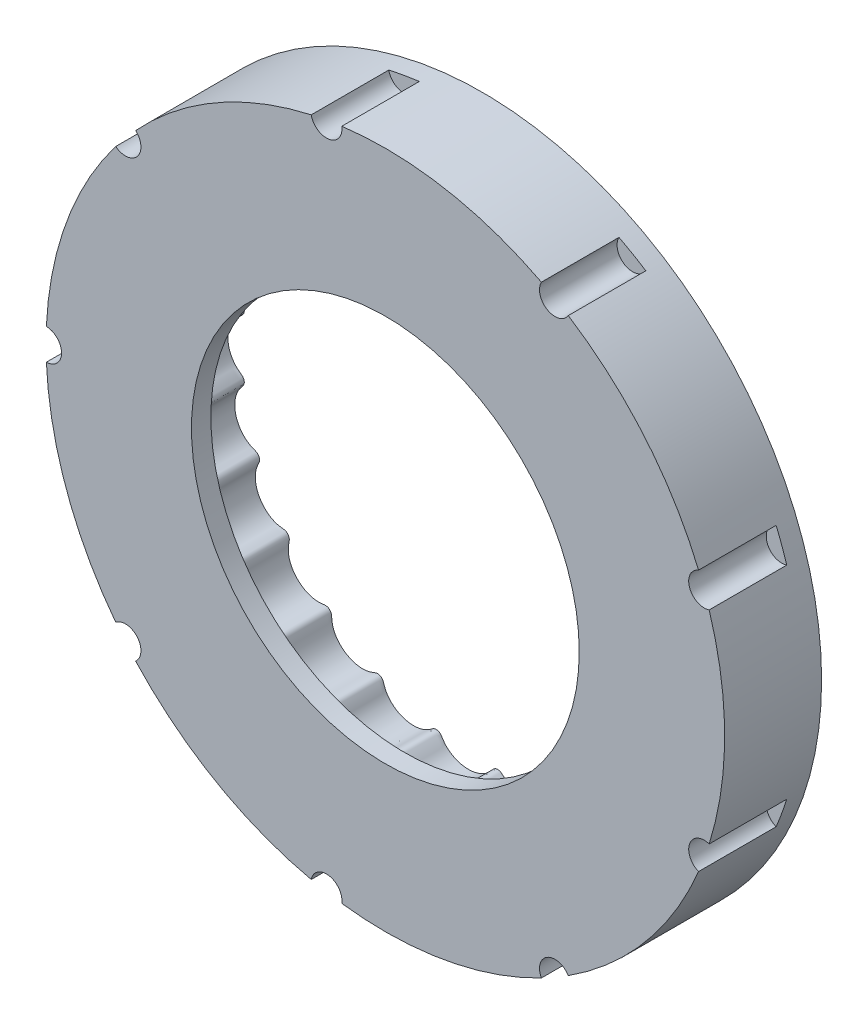
SolidWorks part; units mm, degrees
ref_plane "Plan de face" through (0, 0, 0) normal (0, 0, 1) x (1, 0, 0)
ref_plane "Plan de dessus" through (0, 0, 0) normal (0, 1, 0) x (1, 0, 0)
ref_plane "Plan de droite" through (0, 0, 0) normal (1, 0, 0) x (0, 0, -1)
sketch "Esquisse1" plane through (0, 0, 0) normal (0, 0, 1) x (1, 0, 0)
  line L0 (-1000, 0) -> (49000, 0) construction
  circle A1 centre (0, 0) radius 35
  spline S0 degree 4 poles (24.1426, 6.7991) (24.1177, 6.7609) (24.0692, 6.6836) (24.0004, 6.5645) (23.9483, 6.387) (23.9505, 6.1855) (24.0272, 5.9803) (24.1778, 5.8151) (24.3705, 5.7045) (24.5983, 5.5844) (24.8479, 5.4264) (25.1139, 5.2067) (25.3819, 4.9129) (25.6102, 4.583) (25.7961, 4.2235) (25.9371, 3.8403) (26.0305, 3.4429) (26.0756, 3.0373) (26.0716, 2.6291) (26.0179, 2.2244) (25.9151, 1.834) (25.7643, 1.4641) (25.5917, 1.1641) (25.4167, 0.9296) (25.2526, 0.7496) (25.1124, 0.6144) (24.9828, 0.4987) (24.8797, 0.3844) (24.8179, 0.2829) (24.7848, 0.2051) (24.7673, 0.1461) (24.7588, 0.1043) (24.7529, 0.0597) (24.7496, 0.0145) (24.7496, -0.0147) (24.7529, -0.06) (24.7589, -0.1048) (24.7675, -0.1468) (24.7852, -0.2061) (24.8185, -0.2842) (24.8808, -0.3859) (24.9847, -0.5005) (25.1148, -0.6166) (25.2554, -0.7525) (25.4198, -0.9333) (25.595, -1.1691) (25.7689, -1.4729) (25.9207, -1.8497) (26.0235, -2.2499) (26.0747, -2.6669) (26.0733, -3.0863) (26.0204, -3.5015) (25.917, -3.9063) (25.7644, -4.2943) (25.5662, -4.6548) (25.3259, -4.9815) (25.0816, -5.2331) (24.8519, -5.4186) (24.6671, -5.5402) (24.5395, -5.6139) (24.4102, -5.6846) (24.274, -5.758) (24.12, -5.8678) (23.9899, -6.0503) (23.9364, -6.2751) (23.9692, -6.4958) (24.0654, -6.6843) (24.1784, -6.8519) (24.2801, -7.019) (24.3936, -7.2353) (24.5034, -7.5077) (24.5951, -7.8454) (24.647, -8.2482) (24.6457, -8.6612) (24.576, -9.1855) (24.4176, -9.6961) (24.1747, -10.1766) (23.852, -10.6101) (23.5588, -10.9098) (23.241, -11.1578) (22.9466, -11.3291) (22.6921, -11.4408) (22.4727, -11.5135) (22.2939, -11.5615) (22.1013, -11.606) (21.9021, -11.6816) (21.7285, -11.8281) (21.6209, -12.0388) (21.6016, -12.2637) (21.6505, -12.4693) (21.7183, -12.6598) (21.7746, -12.8471) (21.8297, -13.085) (21.8672, -13.3762) (21.8707, -13.726) (21.8195, -14.1287) (21.7142, -14.528) (21.5148, -15.0178) (21.2331, -15.4721) (20.8771, -15.876) (20.4557, -16.2144) (20.0964, -16.4307) (19.7262, -16.5906) (19.3981, -16.6821) (19.1236, -16.7259) (18.8929, -16.7409) (18.7078, -16.7424) (18.5101, -16.7378) (18.2984, -16.7644) (18.0955, -16.8669) (17.9421, -17.0472) (17.8714, -17.2614) (17.8702, -17.4725) (17.8883, -17.6738) (17.8957, -17.8692) (17.8889, -18.1133) (17.8517, -18.4044) (17.7668, -18.7438) (17.6158, -19.1205) (17.4134, -19.4803) (17.1623, -19.8168) (16.8685, -20.1221) (16.5358, -20.3908) (16.1684, -20.6173) (15.771, -20.7957) (15.3688, -20.9145) (14.9702, -20.976) (14.6296, -20.9817) (14.3529, -20.9549) (14.1259, -20.9112) (13.9464, -20.866) (13.7558, -20.8128) (13.5435, -20.7889) (13.3222, -20.8417) (13.1314, -20.9817) (13.013, -21.1736) (12.9618, -21.3782) (12.9291, -21.5776) (12.887, -21.7685) (12.8188, -22.0029) (12.7093, -22.2752) (12.5416, -22.5821) (12.3006, -22.9086) (12.0142, -23.2057) (11.6866, -23.4682) (11.3255, -23.6897) (10.9359, -23.8661) (10.5233, -23.9928) (10.0937, -24.0655) (9.6744, -24.0792) (9.2731, -24.0382) (8.942, -23.9578) (8.6811, -23.862) (8.4724, -23.7624) (8.31, -23.6735) (8.1383, -23.575) (7.9372, -23.5018) (7.7049, -23.5021) (7.4781, -23.6007) (7.3169, -23.7729) (7.2208, -23.9706) (7.1156, -24.2034) (6.9743, -24.4604) (6.773, -24.7375) (6.4979, -25.0224) (6.1834, -25.2709) (5.8357, -25.4797) (5.4603, -25.6452) (5.0615, -25.7656) (4.6447, -25.8371) (4.2157, -25.8559) (3.7816, -25.8181) (3.3723, -25.7258) (2.9942, -25.5849) (2.6941, -25.4236) (2.4656, -25.2649) (2.2891, -25.1158) (2.1537, -24.9891) (2.0123, -24.8511) (1.8324, -24.7331) (1.553, -24.6659) (1.2621, -24.7546) (1.0754, -24.9576) (0.8891, -25.1941) (0.6967, -25.4018) (0.4476, -25.6153) (0.1257, -25.8218) (-0.2246, -25.9871) (-0.599, -26.1091) (-0.9909, -26.1853) (-1.3919, -26.2146) (-1.7962, -26.1958) (-2.1981, -26.1285) (-2.5915, -26.0119) (-2.9628, -25.849) (-3.3062, -25.6424) (-3.6154, -25.3948) (-3.8503, -25.1456) (-4.0231, -24.9087) (-4.157, -24.6911) (-4.2763, -24.5066) (-4.4563, -24.3545) (-4.6931, -24.2829) (-4.9238, -24.3097) (-5.115, -24.4061) (-5.2732, -24.5252) (-5.423, -24.6339) (-5.6174, -24.7592) (-5.864, -24.8876) (-6.1822, -25.0094) (-6.5751, -25.1011) (-6.9928, -25.1407) (-7.4281, -25.1231) (-7.8512, -25.0501) (-8.2556, -24.9263) (-8.636, -24.7563) (-8.9874, -24.5444) (-9.3058, -24.2932) (-9.5861, -24.0067) (-9.8229, -23.6892) (-9.9872, -23.3887) (-10.0948, -23.1158) (-10.1696, -22.8715) (-10.2411, -22.6635) (-10.3812, -22.4737) (-10.595, -22.3493) (-10.8256, -22.322) (-11.0338, -22.3709) (-11.2164, -22.4474) (-11.3887, -22.5149) (-11.6084, -22.5872) (-11.8793, -22.649) (-12.2179, -22.6866) (-12.6212, -22.6763) (-13.0353, -22.6095) (-13.4521, -22.4829) (-13.8453, -22.3049) (-14.2094, -22.0805) (-14.5395, -21.815) (-14.8313, -21.5131) (-15.0777, -21.1819) (-15.2753, -20.8275) (-15.4026, -20.5017) (-15.4765, -20.2177) (-15.5143, -19.9765) (-15.5318, -19.7817) (-15.5392, -19.5798) (-15.5656, -19.3704) (-15.6608, -19.166) (-15.8341, -19.0047) (-16.0476, -18.9266) (-16.2611, -18.9252) (-16.4568, -18.9543) (-16.6405, -18.9763) (-16.8713, -18.9908) (-17.1491, -18.9822) (-17.4862, -18.9332) (-17.8737, -18.8216) (-18.2576, -18.6527) (-18.6291, -18.4253) (-18.9648, -18.1541) (-19.2607, -17.8454) (-19.5135, -17.5053) (-19.7199, -17.1396) (-19.875, -16.7569) (-19.9769, -16.364) (-20.018, -16.0166) (-20.0178, -15.7231) (-19.9934, -15.4801) (-19.9613, -15.2872) (-19.9181, -15.0898) (-19.894, -14.8799) (-19.9394, -14.6589) (-20.0707, -14.462) (-20.2602, -14.3367) (-20.4672, -14.2852) (-20.6639, -14.2651) (-20.8473, -14.2402) (-21.0742, -14.196) (-21.3408, -14.1175) (-21.6546, -13.985) (-22.0015, -13.7794) (-22.3304, -13.5193) (-22.7055, -13.1302) (-23.0074, -12.6844) (-23.2291, -12.1981) (-23.3648, -11.6869) (-23.4186, -11.2774) (-23.4182, -10.8714) (-23.3703, -10.5248) (-23.296, -10.2407) (-23.211, -10.0117) (-23.1314, -9.8331) (-23.0402, -9.6526) (-22.9672, -9.4541) (-22.9601, -9.2287) (-23.0424, -9.0072) (-23.1982, -8.8407) (-23.3889, -8.7414) (-23.5777, -8.6723) (-23.7531, -8.5999) (-23.9662, -8.4963) (-24.2093, -8.3477) (-24.4803, -8.1356) (-24.7613, -7.8463) (-25.0085, -7.5133) (-25.2666, -7.049) (-25.4429, -6.5476) (-25.5339, -6.0256) (-25.5366, -5.4989) (-25.4855, -5.0889) (-25.3828, -4.696) (-25.2489, -4.3726) (-25.1052, -4.1164) (-24.9652, -3.9162) (-24.8431, -3.7634) (-24.7098, -3.6112) (-24.5919, -3.4354) (-24.5338, -3.2206) (-24.5604, -2.9926) (-24.6667, -2.797) (-24.8227, -2.6537) (-24.9897, -2.5393) (-25.1463, -2.4221) (-25.3325, -2.2638) (-25.5023, -2.0873) (-25.6545, -1.8958) (-25.7905, -1.6883) (-25.89, -1.512) (-25.979, -1.3255) (-26.0566, -1.1315) (-26.1214, -0.9307) (-26.1732, -0.7298) (-26.2073, -0.5457) (-26.2284, -0.3959) (-26.2405, -0.2557) (-26.247, -0.1691) (-26.2503, -0.0328) (-26.2503, 0.0323) (-26.2471, 0.1679) (-26.2407, 0.2542) (-26.2286, 0.3933) (-26.2078, 0.5423) (-26.1742, 0.7251) (-26.123, 0.925) (-26.0591, 1.1245) (-25.9824, 1.3176) (-25.8737, 1.547) (-25.7224, 1.8046) (-25.5451, 2.0414) (-25.3437, 2.2529) (-25.1596, 2.4115) (-25.0044, 2.5289) (-24.8386, 2.6423) (-24.6804, 2.7808) (-24.5546, 2.9935) (-24.5303, 3.2355) (-24.6, 3.4498) (-24.7118, 3.6094) (-24.804, 3.7191) (-24.9086, 3.8447) (-25.0204, 3.9911) (-25.1376, 4.1713) (-25.2521, 4.3886) (-25.3469, 4.6153) (-25.4409, 4.9075) (-25.515, 5.269) (-25.5464, 5.6988) (-25.509, 6.1899) (-25.401, 6.6704) (-25.2688, 7.0153) (-25.1588, 7.235) (-25.0985, 7.3418) knots 0 0 0 0 0 0.001685 0.003369 0.005054 0.006738 0.009006 0.011274 0.013086 0.014899 0.018524 0.022149 0.025774 0.029532 0.03329 0.037047 0.040805 0.044562 0.048319 0.052076 0.055834 0.059425 0.063017 0.064813 0.066609 0.068405 0.070201 0.071231 0.072261 0.072776 0.073291 0.073548 0.073806 0.074321 0.074838 0.075097 0.075356 0.075873 0.07639 0.077425 0.07846 0.080263 0.082066 0.083868 0.085671 0.089277 0.092883 0.09675 0.100617 0.104484 0.108351 0.112188 0.116026 0.119864 0.123701 0.127327 0.130952 0.132764 0.134577 0.135483 0.13639 0.138202 0.140296 0.142389 0.144459 0.146528 0.148331 0.150133 0.151935 0.153737 0.157342 0.160946 0.164812 0.168678 0.172544 0.180416 0.184421 0.188427 0.192432 0.195844 0.199256 0.200962 0.202668 0.204374 0.20608 0.208269 0.210458 0.212527 0.214596 0.216398 0.2182 0.220001 0.221803 0.225407 0.22901 0.232875 0.23674 0.240605 0.248477 0.252483 0.256489 0.260496 0.263908 0.26732 0.269026 0.270732 0.272438 0.274144 0.276335 0.278527 0.280595 0.282663 0.284464 0.286266 0.288067 0.289868 0.293471 0.297074 0.300938 0.304802 0.308666 0.31253 0.316537 0.320545 0.324552 0.328559 0.331971 0.335384 0.33709 0.338796 0.340502 0.342208 0.344401 0.346595 0.348662 0.350729 0.35253 0.354331 0.356132 0.357933 0.361536 0.365138 0.369001 0.372864 0.376727 0.38059 0.384598 0.388606 0.392614 0.396623 0.400035 0.403448 0.405154 0.40686 0.408567 0.410273 0.412468 0.414663 0.416905 0.419148 0.420948 0.422747 0.426346 0.429946 0.433545 0.437321 0.441097 0.444873 0.44865 0.452659 0.456668 0.460677 0.464686 0.468099 0.471512 0.473218 0.474925 0.476631 0.478338 0.480534 0.48273 0.48702 0.488749 0.490478 0.493937 0.497395 0.500854 0.50453 0.508207 0.511883 0.515559 0.519335 0.523111 0.526887 0.530662 0.534262 0.537861 0.54146 0.543259 0.545059 0.547301 0.549542 0.551738 0.553933 0.55564 0.557346 0.559053 0.560759 0.564172 0.567585 0.571593 0.575602 0.57961 0.583619 0.587396 0.591172 0.594949 0.598726 0.602325 0.605924 0.609523 0.611323 0.613123 0.615366 0.61761 0.619804 0.621998 0.623704 0.625411 0.627117 0.628823 0.632235 0.635648 0.639656 0.643663 0.647671 0.651679 0.655542 0.659406 0.663269 0.667133 0.670735 0.674338 0.676139 0.67794 0.679742 0.681543 0.68361 0.685678 0.68787 0.690063 0.691769 0.693475 0.695181 0.696887 0.700299 0.703711 0.707718 0.711725 0.715732 0.719739 0.723603 0.727468 0.731332 0.735197 0.7388 0.742403 0.744204 0.746006 0.747808 0.749609 0.751678 0.753746 0.755937 0.758127 0.759833 0.761539 0.763245 0.764951 0.768363 0.771775 0.775781 0.779787 0.783793 0.791664 0.795529 0.799395 0.80326 0.806864 0.810468 0.81227 0.814073 0.815875 0.817677 0.819746 0.821815 0.823999 0.826183 0.827931 0.82968 0.831429 0.833177 0.836675 0.840172 0.844094 0.848015 0.851937 0.859725 0.863591 0.867458 0.871324 0.874929 0.878534 0.880337 0.882139 0.883942 0.885745 0.887814 0.889884 0.891953 0.894023 0.895826 0.897629 0.899432 0.901235 0.904841 0.906644 0.908448 0.910381 0.912315 0.914249 0.916183 0.918117 0.92005 0.921017 0.921984 0.922951 0.923918 0.924879 0.925839 0.9268 0.927761 0.929682 0.931604 0.933525 0.935447 0.937368 0.93929 0.942875 0.94646 0.948253 0.950045 0.951838 0.95363 0.955683 0.957735 0.960756 0.962266 0.963777 0.964909 0.96604 0.968304 0.970568 0.972832 0.975095 0.977359 0.981887 0.986415 0.990943 0.995472 1 1 1 1 1 construction
  spline S1 degree 4 poles (24.75, 0) (24.75, -0.0119) (24.7507, -0.0298) (24.7529, -0.06) (24.7589, -0.1048) (24.7675, -0.1468) (24.7852, -0.2061) (24.8185, -0.2842) (24.8808, -0.3859) (24.9847, -0.5005) (25.1148, -0.6166) (25.2554, -0.7525) (25.4198, -0.9333) (25.595, -1.1691) (25.7689, -1.4729) (25.9207, -1.8497) (26.0235, -2.2499) (26.0747, -2.6669) (26.0733, -3.0863) (26.0204, -3.5015) (25.917, -3.9063) (25.7644, -4.2943) (25.5662, -4.6548) (25.3259, -4.9815) (25.0816, -5.2331) (24.8519, -5.4186) (24.6671, -5.5402) (24.5395, -5.6139) (24.4102, -5.6846) (24.274, -5.758) (24.12, -5.8678) (23.9899, -6.0503) (23.9364, -6.2751) (23.9692, -6.4958) (24.0654, -6.6843) (24.1784, -6.8519) (24.2801, -7.019) (24.3936, -7.2353) (24.5034, -7.5077) (24.5951, -7.8454) (24.647, -8.2482) (24.6457, -8.6612) (24.576, -9.1855) (24.4176, -9.6961) (24.1747, -10.1766) (23.852, -10.6101) (23.5588, -10.9098) (23.241, -11.1578) (22.9466, -11.3291) (22.6921, -11.4408) (22.4727, -11.5135) (22.2939, -11.5615) (22.1013, -11.606) (21.9021, -11.6816) (21.7285, -11.8281) (21.6209, -12.0388) (21.6016, -12.2637) (21.6505, -12.4693) (21.7183, -12.6598) (21.7746, -12.8471) (21.8297, -13.085) (21.8672, -13.3762) (21.8707, -13.726) (21.8195, -14.1287) (21.7142, -14.528) (21.5148, -15.0178) (21.2331, -15.4721) (20.8771, -15.876) (20.4557, -16.2144) (20.0964, -16.4307) (19.7262, -16.5906) (19.3981, -16.6821) (19.1236, -16.7259) (18.8929, -16.7409) (18.7078, -16.7424) (18.5101, -16.7378) (18.2984, -16.7644) (18.0955, -16.8669) (17.9421, -17.0472) (17.8714, -17.2614) (17.8702, -17.4725) (17.8883, -17.6738) (17.8957, -17.8692) (17.8889, -18.1133) (17.8517, -18.4044) (17.7668, -18.7438) (17.6158, -19.1205) (17.4134, -19.4803) (17.1623, -19.8168) (16.8685, -20.1221) (16.5358, -20.3908) (16.1684, -20.6173) (15.771, -20.7957) (15.3688, -20.9145) (14.9702, -20.976) (14.6296, -20.9817) (14.3529, -20.9549) (14.1259, -20.9112) (13.9464, -20.866) (13.7558, -20.8128) (13.5435, -20.7889) (13.3222, -20.8417) (13.1314, -20.9817) (13.013, -21.1736) (12.9618, -21.3782) (12.9291, -21.5776) (12.887, -21.7685) (12.8188, -22.0029) (12.7093, -22.2752) (12.5416, -22.5821) (12.3006, -22.9086) (12.0142, -23.2057) (11.6866, -23.4682) (11.3255, -23.6897) (10.9359, -23.8661) (10.5233, -23.9928) (10.0937, -24.0655) (9.6744, -24.0792) (9.2731, -24.0382) (8.942, -23.9578) (8.6811, -23.862) (8.4724, -23.7624) (8.31, -23.6735) (8.1383, -23.575) (7.9372, -23.5018) (7.7049, -23.5021) (7.4781, -23.6007) (7.3169, -23.7729) (7.2208, -23.9706) (7.1156, -24.2034) (6.9743, -24.4604) (6.773, -24.7375) (6.4979, -25.0224) (6.1834, -25.2709) (5.8357, -25.4797) (5.4603, -25.6452) (5.0615, -25.7656) (4.6447, -25.8371) (4.2157, -25.8559) (3.7816, -25.8181) (3.3723, -25.7258) (2.9942, -25.5849) (2.6941, -25.4236) (2.4656, -25.2649) (2.2891, -25.1158) (2.1537, -24.9891) (2.0123, -24.8511) (1.8324, -24.7331) (1.553, -24.6659) (1.2621, -24.7546) (1.0754, -24.9576) (0.8891, -25.1941) (0.6967, -25.4018) (0.4476, -25.6153) (0.1257, -25.8218) (-0.2246, -25.9871) (-0.599, -26.1091) (-0.9909, -26.1853) (-1.3919, -26.2146) (-1.7962, -26.1958) (-2.1981, -26.1285) (-2.5915, -26.0119) (-2.9628, -25.849) (-3.3062, -25.6424) (-3.6154, -25.3948) (-3.8503, -25.1456) (-4.0231, -24.9087) (-4.157, -24.6911) (-4.2763, -24.5066) (-4.4563, -24.3545) (-4.6931, -24.2829) (-4.9238, -24.3097) (-5.115, -24.4061) (-5.2732, -24.5252) (-5.423, -24.6339) (-5.6174, -24.7592) (-5.864, -24.8876) (-6.1822, -25.0094) (-6.5751, -25.1011) (-6.9928, -25.1407) (-7.4281, -25.1231) (-7.8512, -25.0501) (-8.2556, -24.9263) (-8.636, -24.7563) (-8.9874, -24.5444) (-9.3058, -24.2932) (-9.5861, -24.0067) (-9.8229, -23.6892) (-9.9872, -23.3887) (-10.0948, -23.1158) (-10.1696, -22.8715) (-10.2411, -22.6635) (-10.3812, -22.4737) (-10.595, -22.3493) (-10.8256, -22.322) (-11.0338, -22.3709) (-11.2164, -22.4474) (-11.3887, -22.5149) (-11.6084, -22.5872) (-11.8793, -22.649) (-12.2179, -22.6866) (-12.6212, -22.6763) (-13.0353, -22.6095) (-13.4521, -22.4829) (-13.8453, -22.3049) (-14.2094, -22.0805) (-14.5395, -21.815) (-14.8313, -21.5131) (-15.0777, -21.1819) (-15.2753, -20.8275) (-15.4026, -20.5017) (-15.4765, -20.2177) (-15.5143, -19.9765) (-15.5318, -19.7817) (-15.5392, -19.5798) (-15.5656, -19.3704) (-15.6608, -19.166) (-15.8341, -19.0047) (-16.0476, -18.9266) (-16.2611, -18.9252) (-16.4568, -18.9543) (-16.6405, -18.9763) (-16.8713, -18.9908) (-17.1491, -18.9822) (-17.4862, -18.9332) (-17.8737, -18.8216) (-18.2576, -18.6527) (-18.6291, -18.4253) (-18.9648, -18.1541) (-19.2607, -17.8454) (-19.5135, -17.5053) (-19.7199, -17.1396) (-19.875, -16.7569) (-19.9769, -16.364) (-20.018, -16.0166) (-20.0178, -15.7231) (-19.9934, -15.4801) (-19.9613, -15.2872) (-19.9181, -15.0898) (-19.894, -14.8799) (-19.9394, -14.6589) (-20.0707, -14.462) (-20.2602, -14.3367) (-20.4672, -14.2852) (-20.6639, -14.2651) (-20.8473, -14.2402) (-21.0742, -14.196) (-21.3408, -14.1175) (-21.6546, -13.985) (-22.0015, -13.7794) (-22.3304, -13.5193) (-22.7055, -13.1302) (-23.0074, -12.6844) (-23.2291, -12.1981) (-23.3648, -11.6869) (-23.4186, -11.2774) (-23.4182, -10.8714) (-23.3703, -10.5248) (-23.296, -10.2407) (-23.211, -10.0117) (-23.1314, -9.8331) (-23.0402, -9.6526) (-22.9672, -9.4541) (-22.9601, -9.2287) (-23.0424, -9.0072) (-23.1982, -8.8407) (-23.3889, -8.7414) (-23.5777, -8.6723) (-23.7531, -8.5999) (-23.9662, -8.4963) (-24.2093, -8.3477) (-24.4803, -8.1356) (-24.7613, -7.8463) (-25.0085, -7.5133) (-25.2666, -7.049) (-25.4429, -6.5476) (-25.5339, -6.0256) (-25.5366, -5.4989) (-25.4855, -5.0889) (-25.3828, -4.696) (-25.2489, -4.3726) (-25.1052, -4.1164) (-24.9652, -3.9162) (-24.8431, -3.7634) (-24.7098, -3.6112) (-24.5919, -3.4354) (-24.5338, -3.2206) (-24.5604, -2.9926) (-24.6667, -2.797) (-24.8227, -2.6537) (-24.9897, -2.5393) (-25.1463, -2.4221) (-25.3325, -2.2638) (-25.5023, -2.0873) (-25.6545, -1.8958) (-25.7905, -1.6883) (-25.89, -1.512) (-25.979, -1.3255) (-26.0566, -1.1315) (-26.1214, -0.9307) (-26.1732, -0.7298) (-26.2073, -0.5457) (-26.2284, -0.3959) (-26.2405, -0.2557) (-26.247, -0.1691) (-26.2495, -0.0667) (-26.25, -0.0223) (-26.25, 0) knots 0.074321 0.074321 0.074321 0.074321 0.074321 0.074838 0.075097 0.075356 0.075873 0.07639 0.077425 0.07846 0.080263 0.082066 0.083868 0.085671 0.089277 0.092883 0.09675 0.100617 0.104484 0.108351 0.112188 0.116026 0.119864 0.123701 0.127327 0.130952 0.132764 0.134577 0.135483 0.13639 0.138202 0.140296 0.142389 0.144459 0.146528 0.148331 0.150133 0.151935 0.153737 0.157342 0.160946 0.164812 0.168678 0.172544 0.180416 0.184421 0.188427 0.192432 0.195844 0.199256 0.200962 0.202668 0.204374 0.20608 0.208269 0.210458 0.212527 0.214596 0.216398 0.2182 0.220001 0.221803 0.225407 0.22901 0.232875 0.23674 0.240605 0.248477 0.252483 0.256489 0.260496 0.263908 0.26732 0.269026 0.270732 0.272438 0.274144 0.276335 0.278527 0.280595 0.282663 0.284464 0.286266 0.288067 0.289868 0.293471 0.297074 0.300938 0.304802 0.308666 0.31253 0.316537 0.320545 0.324552 0.328559 0.331971 0.335384 0.33709 0.338796 0.340502 0.342208 0.344401 0.346595 0.348662 0.350729 0.35253 0.354331 0.356132 0.357933 0.361536 0.365138 0.369001 0.372864 0.376727 0.38059 0.384598 0.388606 0.392614 0.396623 0.400035 0.403448 0.405154 0.40686 0.408567 0.410273 0.412468 0.414663 0.416905 0.419148 0.420948 0.422747 0.426346 0.429946 0.433545 0.437321 0.441097 0.444873 0.44865 0.452659 0.456668 0.460677 0.464686 0.468099 0.471512 0.473218 0.474925 0.476631 0.478338 0.480534 0.48273 0.48702 0.488749 0.490478 0.493937 0.497395 0.500854 0.50453 0.508207 0.511883 0.515559 0.519335 0.523111 0.526887 0.530662 0.534262 0.537861 0.54146 0.543259 0.545059 0.547301 0.549542 0.551738 0.553933 0.55564 0.557346 0.559053 0.560759 0.564172 0.567585 0.571593 0.575602 0.57961 0.583619 0.587396 0.591172 0.594949 0.598726 0.602325 0.605924 0.609523 0.611323 0.613123 0.615366 0.61761 0.619804 0.621998 0.623704 0.625411 0.627117 0.628823 0.632235 0.635648 0.639656 0.643663 0.647671 0.651679 0.655542 0.659406 0.663269 0.667133 0.670735 0.674338 0.676139 0.67794 0.679742 0.681543 0.68361 0.685678 0.68787 0.690063 0.691769 0.693475 0.695181 0.696887 0.700299 0.703711 0.707718 0.711725 0.715732 0.719739 0.723603 0.727468 0.731332 0.735197 0.7388 0.742403 0.744204 0.746006 0.747808 0.749609 0.751678 0.753746 0.755937 0.758127 0.759833 0.761539 0.763245 0.764951 0.768363 0.771775 0.775781 0.779787 0.783793 0.791664 0.795529 0.799395 0.80326 0.806864 0.810468 0.81227 0.814073 0.815875 0.817677 0.819746 0.821815 0.823999 0.826183 0.827931 0.82968 0.831429 0.833177 0.836675 0.840172 0.844094 0.848015 0.851937 0.859725 0.863591 0.867458 0.871324 0.874929 0.878534 0.880337 0.882139 0.883942 0.885745 0.887814 0.889884 0.891953 0.894023 0.895826 0.897629 0.899432 0.901235 0.904841 0.906644 0.908448 0.910381 0.912315 0.914249 0.916183 0.918117 0.92005 0.921017 0.921984 0.922951 0.923918 0.923918 0.923918 0.923918 0.923918
  spline S2 degree 4 poles (24.75, 0) (24.75, 0.0119) (24.7507, 0.0298) (24.7529, 0.06) (24.7589, 0.1048) (24.7675, 0.1468) (24.7852, 0.2061) (24.8185, 0.2842) (24.8808, 0.3859) (24.9847, 0.5005) (25.1148, 0.6166) (25.2554, 0.7525) (25.4198, 0.9333) (25.595, 1.1691) (25.7689, 1.4729) (25.9207, 1.8497) (26.0235, 2.2499) (26.0747, 2.6669) (26.0733, 3.0863) (26.0204, 3.5015) (25.917, 3.9063) (25.7644, 4.2943) (25.5662, 4.6548) (25.3259, 4.9815) (25.0816, 5.2331) (24.8519, 5.4186) (24.6671, 5.5402) (24.5395, 5.6139) (24.4102, 5.6846) (24.274, 5.758) (24.12, 5.8678) (23.9899, 6.0503) (23.9364, 6.2751) (23.9692, 6.4958) (24.0654, 6.6843) (24.1784, 6.8519) (24.2801, 7.019) (24.3936, 7.2353) (24.5034, 7.5077) (24.5951, 7.8454) (24.647, 8.2482) (24.6457, 8.6612) (24.576, 9.1855) (24.4176, 9.6961) (24.1747, 10.1766) (23.852, 10.6101) (23.5588, 10.9098) (23.241, 11.1578) (22.9466, 11.3291) (22.6921, 11.4408) (22.4727, 11.5135) (22.2939, 11.5615) (22.1013, 11.606) (21.9021, 11.6816) (21.7285, 11.8281) (21.6209, 12.0388) (21.6016, 12.2637) (21.6505, 12.4693) (21.7183, 12.6598) (21.7746, 12.8471) (21.8297, 13.085) (21.8672, 13.3762) (21.8707, 13.726) (21.8195, 14.1287) (21.7142, 14.528) (21.5148, 15.0178) (21.2331, 15.4721) (20.8771, 15.876) (20.4557, 16.2144) (20.0964, 16.4307) (19.7262, 16.5906) (19.3981, 16.6821) (19.1236, 16.7259) (18.8929, 16.7409) (18.7078, 16.7424) (18.5101, 16.7378) (18.2984, 16.7644) (18.0955, 16.8669) (17.9421, 17.0472) (17.8714, 17.2614) (17.8702, 17.4725) (17.8883, 17.6738) (17.8957, 17.8692) (17.8889, 18.1133) (17.8517, 18.4044) (17.7668, 18.7438) (17.6158, 19.1205) (17.4134, 19.4803) (17.1623, 19.8168) (16.8685, 20.1221) (16.5358, 20.3908) (16.1684, 20.6173) (15.771, 20.7957) (15.3688, 20.9145) (14.9702, 20.976) (14.6296, 20.9817) (14.3529, 20.9549) (14.1259, 20.9112) (13.9464, 20.866) (13.7558, 20.8128) (13.5435, 20.7889) (13.3222, 20.8417) (13.1314, 20.9817) (13.013, 21.1736) (12.9618, 21.3782) (12.9291, 21.5776) (12.887, 21.7685) (12.8188, 22.0029) (12.7093, 22.2752) (12.5416, 22.5821) (12.3006, 22.9086) (12.0142, 23.2057) (11.6866, 23.4682) (11.3255, 23.6897) (10.9359, 23.8661) (10.5233, 23.9928) (10.0937, 24.0655) (9.6744, 24.0792) (9.2731, 24.0382) (8.942, 23.9578) (8.6811, 23.862) (8.4724, 23.7624) (8.31, 23.6735) (8.1383, 23.575) (7.9372, 23.5018) (7.7049, 23.5021) (7.4781, 23.6007) (7.3169, 23.7729) (7.2208, 23.9706) (7.1156, 24.2034) (6.9743, 24.4604) (6.773, 24.7375) (6.4979, 25.0224) (6.1834, 25.2709) (5.8357, 25.4797) (5.4603, 25.6452) (5.0615, 25.7656) (4.6447, 25.8371) (4.2157, 25.8559) (3.7816, 25.8181) (3.3723, 25.7258) (2.9942, 25.5849) (2.6941, 25.4236) (2.4656, 25.2649) (2.2891, 25.1158) (2.1537, 24.9891) (2.0123, 24.8511) (1.8324, 24.7331) (1.553, 24.6659) (1.2621, 24.7546) (1.0754, 24.9576) (0.8891, 25.1941) (0.6967, 25.4018) (0.4476, 25.6153) (0.1257, 25.8218) (-0.2246, 25.9871) (-0.599, 26.1091) (-0.9909, 26.1853) (-1.3919, 26.2146) (-1.7962, 26.1958) (-2.1981, 26.1285) (-2.5915, 26.0119) (-2.9628, 25.849) (-3.3062, 25.6424) (-3.6154, 25.3948) (-3.8503, 25.1456) (-4.0231, 24.9087) (-4.157, 24.6911) (-4.2763, 24.5066) (-4.4563, 24.3545) (-4.6931, 24.2829) (-4.9238, 24.3097) (-5.115, 24.4061) (-5.2732, 24.5252) (-5.423, 24.6339) (-5.6174, 24.7592) (-5.864, 24.8876) (-6.1822, 25.0094) (-6.5751, 25.1011) (-6.9928, 25.1407) (-7.4281, 25.1231) (-7.8512, 25.0501) (-8.2556, 24.9263) (-8.636, 24.7563) (-8.9874, 24.5444) (-9.3058, 24.2932) (-9.5861, 24.0067) (-9.8229, 23.6892) (-9.9872, 23.3887) (-10.0948, 23.1158) (-10.1696, 22.8715) (-10.2411, 22.6635) (-10.3812, 22.4737) (-10.595, 22.3493) (-10.8256, 22.322) (-11.0338, 22.3709) (-11.2164, 22.4474) (-11.3887, 22.5149) (-11.6084, 22.5872) (-11.8793, 22.649) (-12.2179, 22.6866) (-12.6212, 22.6763) (-13.0353, 22.6095) (-13.4521, 22.4829) (-13.8453, 22.3049) (-14.2094, 22.0805) (-14.5395, 21.815) (-14.8313, 21.5131) (-15.0777, 21.1819) (-15.2753, 20.8275) (-15.4026, 20.5017) (-15.4765, 20.2177) (-15.5143, 19.9765) (-15.5318, 19.7817) (-15.5392, 19.5798) (-15.5656, 19.3704) (-15.6608, 19.166) (-15.8341, 19.0047) (-16.0476, 18.9266) (-16.2611, 18.9252) (-16.4568, 18.9543) (-16.6405, 18.9763) (-16.8713, 18.9908) (-17.1491, 18.9822) (-17.4862, 18.9332) (-17.8737, 18.8216) (-18.2576, 18.6527) (-18.6291, 18.4253) (-18.9648, 18.1541) (-19.2607, 17.8454) (-19.5135, 17.5053) (-19.7199, 17.1396) (-19.875, 16.7569) (-19.9769, 16.364) (-20.018, 16.0166) (-20.0178, 15.7231) (-19.9934, 15.4801) (-19.9613, 15.2872) (-19.9181, 15.0898) (-19.894, 14.8799) (-19.9394, 14.6589) (-20.0707, 14.462) (-20.2602, 14.3367) (-20.4672, 14.2852) (-20.6639, 14.2651) (-20.8473, 14.2402) (-21.0742, 14.196) (-21.3408, 14.1175) (-21.6546, 13.985) (-22.0015, 13.7794) (-22.3304, 13.5193) (-22.7055, 13.1302) (-23.0074, 12.6844) (-23.2291, 12.1981) (-23.3648, 11.6869) (-23.4186, 11.2774) (-23.4182, 10.8714) (-23.3703, 10.5248) (-23.296, 10.2407) (-23.211, 10.0117) (-23.1314, 9.8331) (-23.0402, 9.6526) (-22.9672, 9.4541) (-22.9601, 9.2287) (-23.0424, 9.0072) (-23.1982, 8.8407) (-23.3889, 8.7414) (-23.5777, 8.6723) (-23.7531, 8.5999) (-23.9662, 8.4963) (-24.2093, 8.3477) (-24.4803, 8.1356) (-24.7613, 7.8463) (-25.0085, 7.5133) (-25.2666, 7.049) (-25.4429, 6.5476) (-25.5339, 6.0256) (-25.5366, 5.4989) (-25.4855, 5.0889) (-25.3828, 4.696) (-25.2489, 4.3726) (-25.1052, 4.1164) (-24.9652, 3.9162) (-24.8431, 3.7634) (-24.7098, 3.6112) (-24.5919, 3.4354) (-24.5338, 3.2206) (-24.5604, 2.9926) (-24.6667, 2.797) (-24.8227, 2.6537) (-24.9897, 2.5393) (-25.1463, 2.4221) (-25.3325, 2.2638) (-25.5023, 2.0873) (-25.6545, 1.8958) (-25.7905, 1.6883) (-25.89, 1.512) (-25.979, 1.3255) (-26.0566, 1.1315) (-26.1214, 0.9307) (-26.1732, 0.7298) (-26.2073, 0.5457) (-26.2284, 0.3959) (-26.2405, 0.2557) (-26.247, 0.1691) (-26.2495, 0.0667) (-26.25, 0.0223) (-26.25, 0) knots 0.074321 0.074321 0.074321 0.074321 0.074321 0.074838 0.075097 0.075356 0.075873 0.07639 0.077425 0.07846 0.080263 0.082066 0.083868 0.085671 0.089277 0.092883 0.09675 0.100617 0.104484 0.108351 0.112188 0.116026 0.119864 0.123701 0.127327 0.130952 0.132764 0.134577 0.135483 0.13639 0.138202 0.140296 0.142389 0.144459 0.146528 0.148331 0.150133 0.151935 0.153737 0.157342 0.160946 0.164812 0.168678 0.172544 0.180416 0.184421 0.188427 0.192432 0.195844 0.199256 0.200962 0.202668 0.204374 0.20608 0.208269 0.210458 0.212527 0.214596 0.216398 0.2182 0.220001 0.221803 0.225407 0.22901 0.232875 0.23674 0.240605 0.248477 0.252483 0.256489 0.260496 0.263908 0.26732 0.269026 0.270732 0.272438 0.274144 0.276335 0.278527 0.280595 0.282663 0.284464 0.286266 0.288067 0.289868 0.293471 0.297074 0.300938 0.304802 0.308666 0.31253 0.316537 0.320545 0.324552 0.328559 0.331971 0.335384 0.33709 0.338796 0.340502 0.342208 0.344401 0.346595 0.348662 0.350729 0.35253 0.354331 0.356132 0.357933 0.361536 0.365138 0.369001 0.372864 0.376727 0.38059 0.384598 0.388606 0.392614 0.396623 0.400035 0.403448 0.405154 0.40686 0.408567 0.410273 0.412468 0.414663 0.416905 0.419148 0.420948 0.422747 0.426346 0.429946 0.433545 0.437321 0.441097 0.444873 0.44865 0.452659 0.456668 0.460677 0.464686 0.468099 0.471512 0.473218 0.474925 0.476631 0.478338 0.480534 0.48273 0.48702 0.488749 0.490478 0.493937 0.497395 0.500854 0.50453 0.508207 0.511883 0.515559 0.519335 0.523111 0.526887 0.530662 0.534262 0.537861 0.54146 0.543259 0.545059 0.547301 0.549542 0.551738 0.553933 0.55564 0.557346 0.559053 0.560759 0.564172 0.567585 0.571593 0.575602 0.57961 0.583619 0.587396 0.591172 0.594949 0.598726 0.602325 0.605924 0.609523 0.611323 0.613123 0.615366 0.61761 0.619804 0.621998 0.623704 0.625411 0.627117 0.628823 0.632235 0.635648 0.639656 0.643663 0.647671 0.651679 0.655542 0.659406 0.663269 0.667133 0.670735 0.674338 0.676139 0.67794 0.679742 0.681543 0.68361 0.685678 0.68787 0.690063 0.691769 0.693475 0.695181 0.696887 0.700299 0.703711 0.707718 0.711725 0.715732 0.719739 0.723603 0.727468 0.731332 0.735197 0.7388 0.742403 0.744204 0.746006 0.747808 0.749609 0.751678 0.753746 0.755937 0.758127 0.759833 0.761539 0.763245 0.764951 0.768363 0.771775 0.775781 0.779787 0.783793 0.791664 0.795529 0.799395 0.80326 0.806864 0.810468 0.81227 0.814073 0.815875 0.817677 0.819746 0.821815 0.823999 0.826183 0.827931 0.82968 0.831429 0.833177 0.836675 0.840172 0.844094 0.848015 0.851937 0.859725 0.863591 0.867458 0.871324 0.874929 0.878534 0.880337 0.882139 0.883942 0.885745 0.887814 0.889884 0.891953 0.894023 0.895826 0.897629 0.899432 0.901235 0.904841 0.906644 0.908448 0.910381 0.912315 0.914249 0.916183 0.918117 0.92005 0.921017 0.921984 0.922951 0.923918 0.923918 0.923918 0.923918 0.923918
  dimension "D1" = 70
extrude "Boss.-Extru.1" add sketch "Esquisse1" along normal blind 8
sketch "Esquisse3" plane through (0, 0, 8) normal (0, 0, 1) x (1, 0, 0)
  circle A0 centre (0, 0) radius 20
  circle A1 centre (0, 0) radius 35
  circle A2 centre (0, 0) radius 35 construction
  dimension "D1" = 40
extrude "Boss.-Extru.2" add sketch "Esquisse3" along normal blind 2
sketch "Esquisse4" plane through (0, 0, 10) normal (0, 0, 1) x (1, 0, 0)
  circle A0 centre (-35, 0) radius 1.6
  circle A1 centre (0, 0) radius 35 construction
  circle A2 centre (-26.8116, 22.4976) radius 1.6
  circle A3 centre (-6.0777, 34.4683) radius 1.6
  circle A4 centre (17.5, 30.3109) radius 1.6
  circle A5 centre (32.8892, 11.9707) radius 1.6
  circle A6 centre (32.8892, -11.9707) radius 1.6
  circle A7 centre (17.5, -30.3109) radius 1.6
  circle A8 centre (-6.0777, -34.4683) radius 1.6
  circle A9 centre (-26.8116, -22.4976) radius 1.6
  point P24 (0, 0)
  dimension "D1" = 3.2
extrude "Enlèv. mat.-Extru.2" cut sketch "Esquisse4" against normal blind 8
equation "\"R\"= 26'Radius of the rotor"
equation "\"E\"= 0.75'Eccentricity from input shaft to center of rotor"
equation "\"Rr\"= 0.5'Roller radius"
equation "\"N\"= 26'Amount of rollers"
